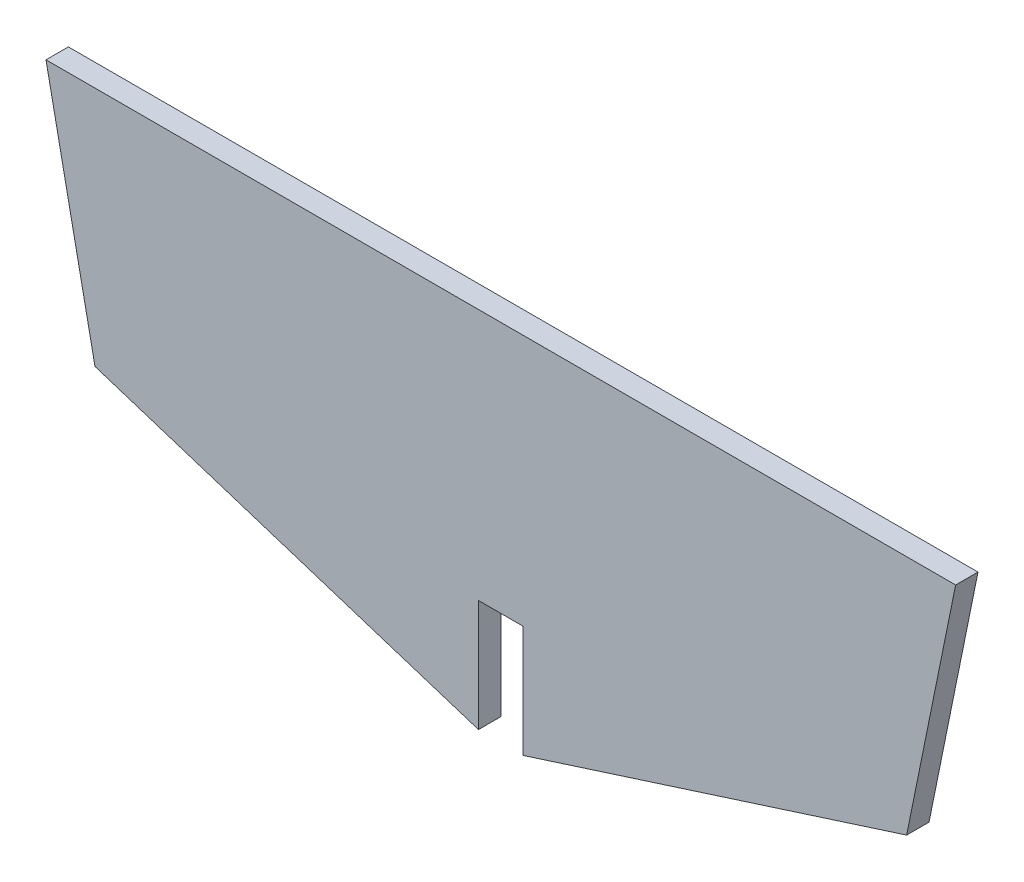
SolidWorks part; units mm, degrees
ref_plane "Plan de face" through (0, 0, 0) normal (0, 0, 1) x (1, 0, 0)
ref_plane "Plan de dessus" through (0, 0, 0) normal (0, 1, 0) x (1, 0, 0)
ref_plane "Plan de droite" through (0, 0, 0) normal (1, 0, 0) x (0, 0, -1)
sketch "Esquisse1" plane through (0, 0, 0) normal (0, 0, 1) x (1, 0, 0)
  line L0 (-26.4234, 16.4316) -> (95.5766, 16.4316)
  line L1 (-26.4234, 16.4316) -> (-19.8534, -15.9078)
  line L2 (-19.8534, -15.9078) -> (31.5766, -32.3684)
  line L3 (31.5766, -32.3684) -> (31.5766, -17.3684)
  line L4 (31.5766, -17.3684) -> (37.5766, -17.3684)
  line L5 (34.5766, 16.4316) -> (34.5766, -17.3684) construction
  line L6 (37.5766, -32.3684) -> (37.5766, -17.3684)
  line L7 (89.0066, -15.9078) -> (37.5766, -32.3684)
  line L8 (95.5766, 16.4316) -> (89.0066, -15.9078)
  dimension "D1" = 61
  dimension "D2" = 33
  dimension "D3" = 54
  dimension "D4" = 6
  dimension "D5" = 15
  dimension "D6" = 33.8
extrude "Boss.-Extru.1" add sketch "Esquisse1" along normal blind 3
